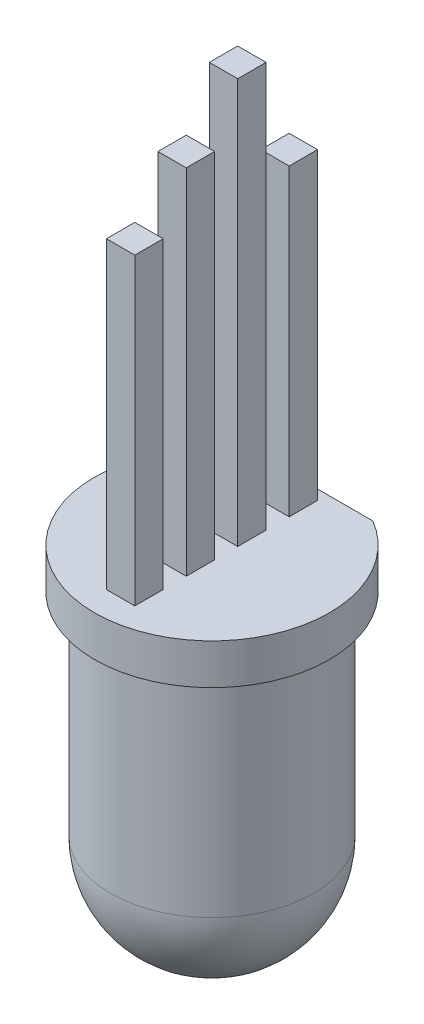
SolidWorks part; units mm, degrees
ref_plane "Plan de face" through (0, 0, 0) normal (0, 0, 1) x (1, 0, 0)
ref_plane "Plan de dessus" through (0, 0, 0) normal (0, 1, 0) x (1, 0, 0)
ref_plane "Plan de droite" through (0, 0, 0) normal (1, 0, 0) x (0, 0, -1)
sketch "Esquisse1" plane through (0, 0, 0) normal (0, 0, 1) x (1, 0, 0)
  line L0 (2.5, 7.7) -> (2.5, 2.5)
  line L1 (2.5, 7.7) -> (2.9, 7.7)
  line L2 (2.9, 7.7) -> (2.9, 8.7)
  line L3 (2.9, 8.7) -> (0, 8.7)
  line L4 (0, 0) -> (0, 10.615) construction
  line L5 (0, 0) -> (0, 8.7)
  arc A0 (2.5, 2.5) -> (0, 0) centre (0, 2.5) cw
  dimension "D1" = 2.5
  dimension "D2" = 7.7
  dimension "D3" = 90
  dimension "D4" = 0.4
  dimension "D5" = 1
  dimension "D6" = 5.8
revolve "Révolution1" add sketch "Esquisse1" angle 360 about L4
sketch "Esquisse2" plane through (0, 7.7, 0) normal (0, -1, 0) x (-1, 0, 0)
  line L0 (2.0316, 2.5) -> (-2.1192, 2.5)
  line L1 (2.0316, 2.5) -> (-0.3043, 5.4158)
  line L2 (-0.3043, 5.4158) -> (-2.1192, 2.5)
  circle A0 centre (0, 0) radius 2.5 construction
extrude "Enlèv. mat.-Extru.1" cut sketch "Esquisse2" against normal up to next
sketch "Esquisse3" plane through (0, 8.7, 0) normal (0, 1, 0) x (1, 0, 0)
  line L0 (-0.35, 2.255) -> (0.35, 2.255)
  line L1 (0.35, 2.255) -> (0.35, 1.555)
  line L2 (0.35, 1.555) -> (-0.35, 1.555)
  line L3 (-0.35, 1.555) -> (-0.35, 2.255)
  line L4 (-0.35, -0.985) -> (0.35, -0.985)
  line L5 (0.35, -0.985) -> (0.35, -0.285)
  line L6 (0.35, -0.285) -> (-0.35, -0.285)
  line L7 (-0.35, -0.285) -> (-0.35, -0.985)
  line L8 (-0.35, -1.555) -> (0.35, -1.555)
  line L9 (0.35, -1.555) -> (0.35, -2.255)
  line L10 (0.35, -2.255) -> (-0.35, -2.255)
  line L11 (-0.35, -2.255) -> (-0.35, -1.555)
  line L12 (-0.35, 0.985) -> (0.35, 0.985)
  line L13 (0.35, 0.985) -> (0.35, 0.285)
  line L14 (0.35, 0.285) -> (-0.35, 0.285)
  line L15 (-0.35, 0.285) -> (-0.35, 0.985)
  line L16 (0, 2.8041) -> (0, -3.2431) construction
  dimension "D1" = 0.7
  dimension "D2" = 0.7
  dimension "D3" = 0.35
  dimension "D4" = 0.35
  dimension "D5" = 0.35
  dimension "D6" = 0.7
  dimension "D7" = 0.7
  dimension "D8" = 0.7
  dimension "D9" = 0.7
  dimension "D10" = 0.35
  dimension "D11" = 1.27
  dimension "D12" = 0.7
  dimension "D13" = 0.7
  dimension "D14" = 1.27
  dimension "D15" = 1.27
  dimension "D16" = 0.285
extrude "Boss.-Extru.1" add sketch "Esquisse3" along normal blind 10
sketch "Esquisse4" plane through (-0.35, 0, 0) normal (-1, 0, 0) x (0, 0, 1)
  line L0 (-2.8851, 16.2) -> (-1.2657, 16.2)
  line L1 (-1.2657, 16.2) -> (-1.2657, 33.9219)
  line L2 (-1.2657, 33.9219) -> (0, 33.9219)
  line L3 (0, 33.9219) -> (0, 17.43)
  line L4 (0, 17.43) -> (1.3444, 17.43)
  line L5 (1.3444, 17.43) -> (1.3444, 16.2)
  line L6 (1.3444, 16.2) -> (2.8975, 16.2)
  line L7 (2.8975, 16.2) -> (2.8975, 34.6769)
  line L8 (2.8975, 34.6769) -> (-2.8851, 34.6769)
  line L9 (-2.8851, 34.6769) -> (-2.8851, 16.2)
  line L10 (-0.985, 18.7) -> (-0.285, 18.7) construction
  line L11 (0.285, 18.7) -> (0.985, 18.7) construction
  dimension "D1" = 2.5
  dimension "D2" = 2.5
  dimension "D3" = 1.27
extrude "Enlèv. mat.-Extru.2" cut sketch "Esquisse4" against normal up to next
